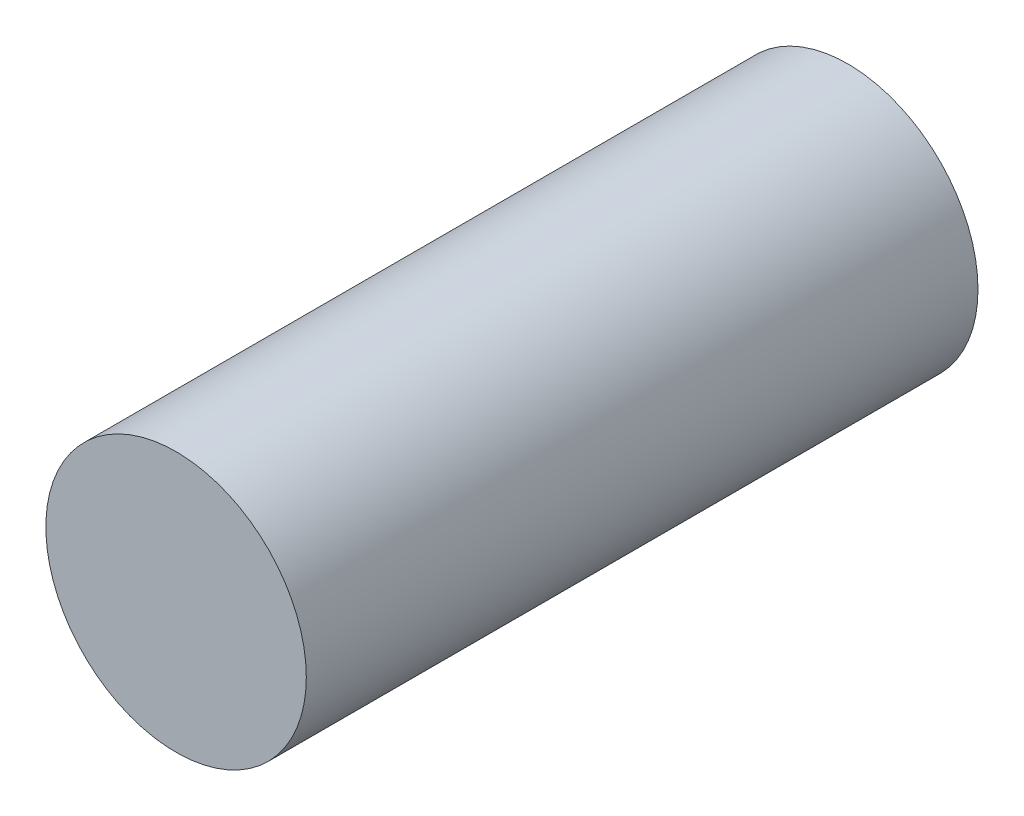
SolidWorks part; units mm, degrees
material "Payload"
ref_plane "Front Plane" through (0, 0, 0) normal (0, 0, 1) x (1, 0, 0)
ref_plane "Top Plane" through (0, 0, 0) normal (0, 1, 0) x (1, 0, 0)
ref_plane "Right Plane" through (0, 0, 0) normal (1, 0, 0) x (0, 0, -1)
sketch "Sketch1" plane through (0, 0, 0) normal (0, 0, 1) x (1, 0, 0)
  circle A0 centre (0, 0) radius 19
  dimension "D1" = 38
extrude "Boss-Extrude1" add sketch "Sketch1" along normal blind 98 contours A0
